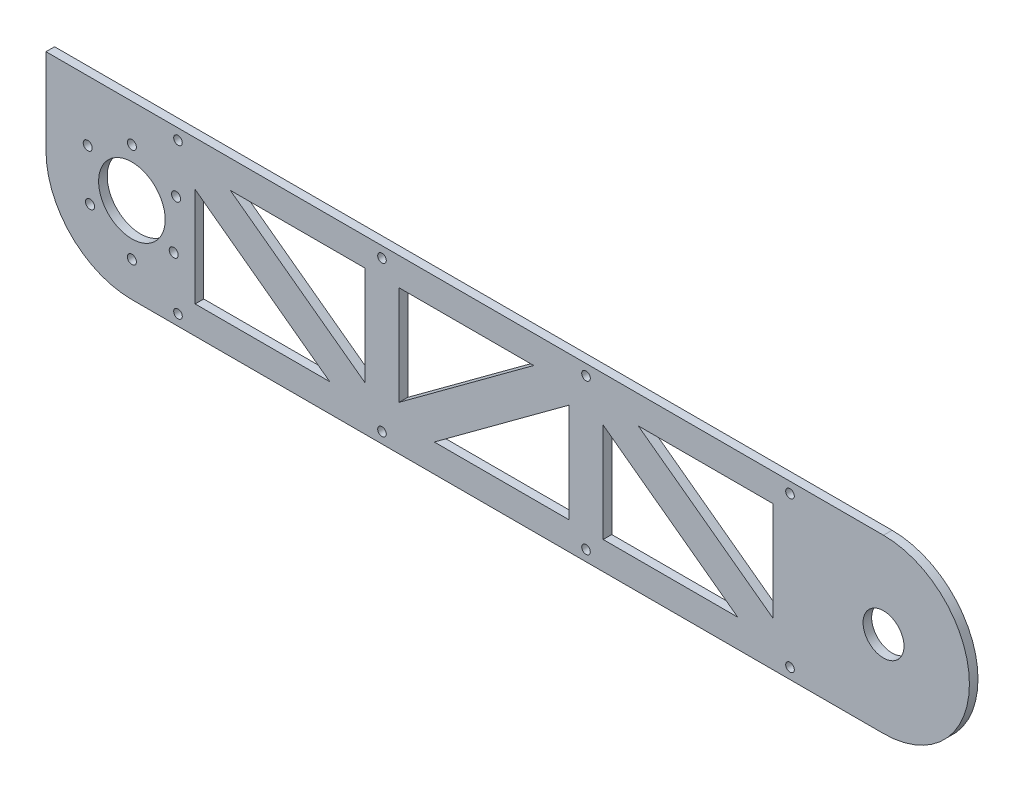
SolidWorks part; units mm, degrees
ref_plane "前视基准面" through (0, 0, 0) normal (0, 0, 1) x (1, 0, 0)
ref_plane "上视基准面" through (0, 0, 0) normal (0, 1, 0) x (1, 0, 0)
ref_plane "右视基准面" through (0, 0, 0) normal (1, 0, 0) x (0, 0, -1)
sketch "草图1" plane through (0, 0, 0) normal (0, 0, 1) x (1, 0, 0)
  line L0 (-1.4571, -0.1457) -> (37.8152, -22.8196) construction
  line L1 (-1.4571, -0.1457) -> (348.5429, -0.1457) construction
  line L3 (-1.4571, -40.1457) -> (348.5429, -40.1457)
  line L6 (14.0429, 39.8543) -> (348.5429, 39.8543)
  line L7 (14.0429, 39.8543) -> (-1.4571, 39.8543)
  circle A0 centre (-1.4571, -0.1457) radius 23.75 construction
  circle A1 centre (-1.4571, -0.1457) radius 22.5 construction
  circle A2 centre (-1.4571, -23.8957) radius 2.1
  circle A3 centre (18.0284, -11.3957) radius 2.1
  circle A4 centre (-1.4571, -0.1457) radius 40 construction
  circle A6 centre (-1.4571, -0.1457) radius 15.5
  circle A11 centre (348.5429, -0.1457) radius 9.53
  circle A12 centre (348.5429, -0.1457) radius 40 construction
  arc A13 (348.5429, 39.8543) -> (348.5429, -40.1457) centre (348.5429, -0.1457) cw
  arc A16 (-1.4571, -40.1457) -> (-1.4571, 39.8543) centre (-1.4571, -0.1457) cw
  circle A17 centre (-22.0252, 11.7293) radius 2.1
  circle A18 centre (-20.9427, -11.3957) radius 2.1
  circle A19 centre (19.111, 11.7293) radius 2.1
  circle A20 centre (-1.4571, 22.3543) radius 2.1
  dimension "D1" = 45
  dimension "D2" = 3
  dimension "D3" = 4.2
  dimension "D4" = 19.06
  dimension "D5" = 80
  dimension "D6" = 80
extrude "凸台-拉伸1" add sketch "草图1" along normal blind 4 contours L3 A13 L6
sketch "草图2" plane through (0, 0, 0) normal (0, 0, -1) x (-1, 0, 0)
  line L0 (-210, 34.8543) -> (-305, -35.1457) construction
  line L1 (-218, -27.1457) -> (-280.6567, -27.1457)
  line L2 (-218, 19.0223) -> (-280.6567, -27.1457)
  line L3 (-218, 19.0223) -> (-218, -27.1457)
  line L4 (-305, -35.1457) -> (-305, 34.8543) construction
  line L5 (-234.3433, 26.8543) -> (-297, -19.3138)
  line L12 (-297, -19.3138) -> (-297, 26.8543)
  line L13 (-234.3433, 26.8543) -> (-297, 26.8543)
  line L48 (-210, -35.1457) -> (-305, -35.1457) construction
  line L51 (-210, 34.8543) -> (-305, 34.8543) construction
  line L52 (-115, 34.8543) -> (-210, 34.8543) construction
  line L53 (-210, -35.1457) -> (-115, -35.1457) construction
  line L54 (-210, 34.8543) -> (-210, -35.1457) construction
  line L55 (-20, 34.8543) -> (-20, -35.1457) construction
  line L56 (-20, -35.1457) -> (-115, -35.1457) construction
  line L57 (-115, -35.1457) -> (-20, 34.8543) construction
  line L58 (-115, 34.8543) -> (-115, -35.1457) construction
  line L59 (-20, 34.8543) -> (-115, 34.8543) construction
  line L60 (1.4571, -0.1457) -> (-348.5429, -0.1457) construction
  line L72 (-123, 26.8543) -> (-123, -19.3138)
  line L73 (-123, -19.3138) -> (-185.6567, 26.8543)
  line L74 (-123, 26.8543) -> (-185.6567, 26.8543)
  line L75 (-202, -27.1457) -> (-139.3433, -27.1457)
  line L76 (-202, 19.0223) -> (-202, -27.1457)
  line L77 (-139.3433, -27.1457) -> (-202, 19.0223)
  line L78 (-115, -35.1457) -> (-210, 34.8543) construction
  line L79 (-90.6567, -27.1457) -> (-28, 19.0223)
  line L80 (-28, -27.1457) -> (-90.6567, -27.1457)
  line L81 (-28, 19.0223) -> (-28, -27.1457)
  line L82 (-107, -19.3138) -> (-44.3433, 26.8543)
  line L83 (-107, 26.8543) -> (-107, -19.3138)
  line L84 (-44.3433, 26.8543) -> (-107, 26.8543)
  circle A8 centre (-20, -35.1457) radius 2
  circle A9 centre (-115, -35.1457) radius 2
  circle A10 centre (-210, -35.1457) radius 2
  circle A11 centre (-305, -35.1457) radius 2
  circle A12 centre (-305, 34.8543) radius 2
  circle A13 centre (-210, 34.8543) radius 2
  circle A14 centre (-115, 34.8543) radius 2
  circle A15 centre (-20, 34.8543) radius 2
  dimension "D1" = 8
  dimension "D2" = 8
extrude "切除-拉伸1" cut sketch "草图2" against normal blind 10
sketch "草图3" plane through (0, 0, 0) normal (0, 0, -1) x (-1, 0, 0)
  line L0 (1.4571, 39.8543) -> (35.6089, 39.8543)
  line L1 (35.6089, 39.8543) -> (41.4571, 39.8543)
  line L2 (41.4571, 39.8543) -> (41.4571, -0.1457)
  line L3 (41.4571, -0.1457) -> (1.4571, 39.8543)
  arc A0 (1.4571, -40.1457) -> (1.4571, 39.8543) centre (1.4571, -0.1457) ccw construction
extrude "凸台-拉伸2" add sketch "草图3" against normal blind 4
